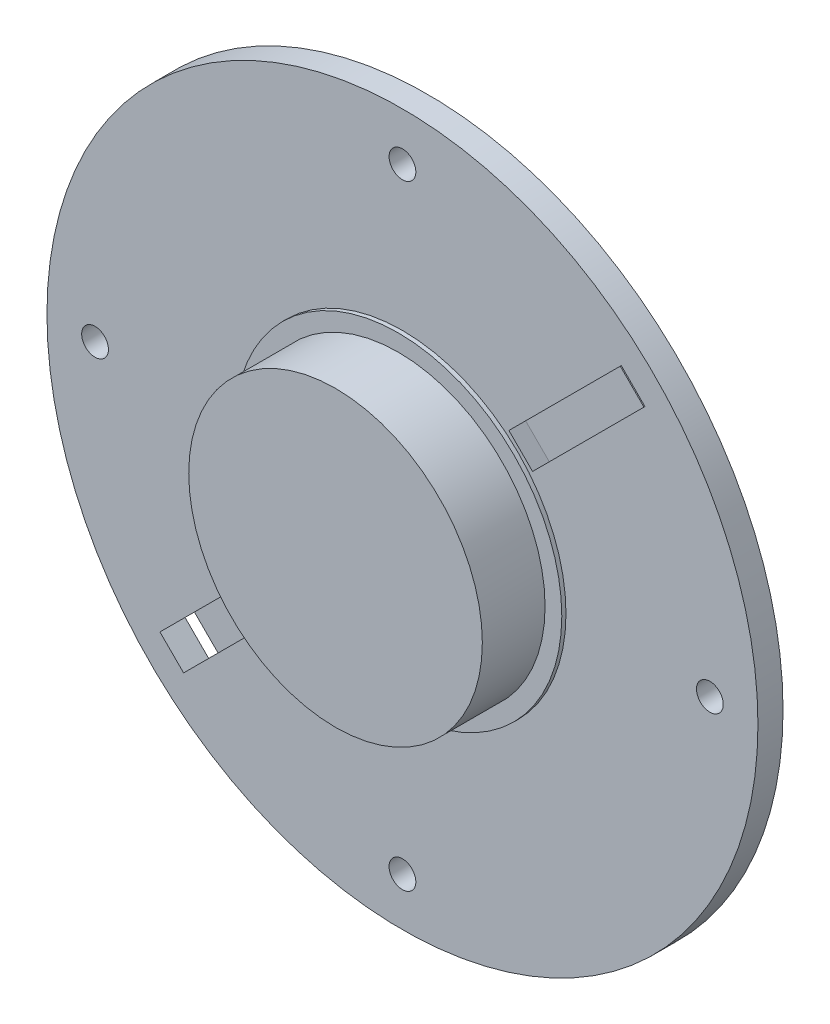
SolidWorks part; units mm, degrees
ref_plane "Front Plane" through (0, 0, 0) normal (0, 0, 1) x (1, 0, 0)
ref_plane "Top Plane" through (0, 0, 0) normal (0, 1, 0) x (1, 0, 0)
ref_plane "Right Plane" through (0, 0, 0) normal (1, 0, 0) x (0, 0, -1)
sketch "Sketch1" plane through (0, 0, 0) normal (1, 0, 0) x (0, 0, -1)
  line L0 (0, 0) -> (0, 42.5)
  line L1 (0, 42.5) -> (-3, 42.5)
  line L2 (-3, 42.5) -> (-3, 19.55)
  line L3 (-3.5, 17.55) -> (-11, 17.55)
  line L4 (-11, 17.55) -> (-11, 0)
  line L5 (-11, 0) -> (0, 0)
  line L6 (0, 0) -> (-73.6158, 0) construction
  line L7 (-3.5, 17.55) -> (-3.5, 19.55)
  line L8 (-3.5, 19.55) -> (-3, 19.55)
  dimension "D1" = 35.1
  dimension "D2" = 85
  dimension "D3" = 3
  dimension "D4" = 8
  dimension "D5" = 0.5
  dimension "D6" = 2
revolve "Revolve1" add sketch "Sketch1" angle 360 about L5
sketch "Sketch2" plane through (0, 0, 0) normal (0, 0, -1) x (-1, 0, 0)
  circle A0 centre (0, 0) radius 36.75 construction
  circle A1 centre (0, 36.75) radius 1.6
  circle A2 centre (36.75, 0) radius 1.6
  circle A3 centre (0, -36.75) radius 1.6
  circle A4 centre (-36.75, 0) radius 1.6
  point P11 (0, 0)
  dimension "D3" = 3.2
extrude "Cut-Extrude1" cut sketch "Sketch2" against normal through all
sketch "Sketch3" [suppressed] plane through (0, 0, 11) normal (0, 0, 1) x (1, 0, 0)
  line L0 (0, -4) -> (0, 4) construction
  line L2 (9, -9) -> (-9, -9) construction
  line L3 (9, -9) -> (9, 9) construction
  line L4 (9, 9) -> (-9, 9) construction
  line L5 (-9, -9) -> (-9, 9) construction
  line L6 (9, -9) -> (-9, 9) construction
  line L7 (9, 9) -> (-9, -9) construction
  circle A0 centre (0, 4) radius 2.4
  circle A1 centre (0, -4) radius 2.4
  circle A2 centre (-9, 9) radius 2.4
  circle A3 centre (9, 9) radius 2.4
  circle A4 centre (9, -9) radius 2.4
  circle A5 centre (-9, -9) radius 2.4
  point P0 (0, 0)
  point P10 (0, 0)
  dimension "D1" = 4.8
  dimension "D3" = 4.8
  dimension "8" = 8
  dimension "D4" = 18
extrude "Cut-Extrude2" [suppressed] cut sketch "Sketch3" against normal blind 4
sketch "Sketch5" [suppressed] plane through (0, 0, 3) normal (0, 0, -1) x (-1, 0, 0)
  line L0 (-5.1962, 34.5) -> (-32.476, -12.75)
  line L6 (5.1962, 34.5) -> (32.476, -12.75)
  line L7 (-27.2798, -21.75) -> (27.2798, -21.75)
  arc A0 (5.1962, 34.5) -> (-5.1962, 34.5) centre (0, 31.5) ccw
  arc A1 (-32.476, -12.75) -> (-27.2798, -21.75) centre (-27.2798, -15.75) ccw
  arc A2 (27.2798, -21.75) -> (32.476, -12.75) centre (27.2798, -15.75) ccw
  circle A3 centre (0, 0) radius 17.55 construction
  circle A4 centre (0, 0) radius 17.55 construction
  dimension "D1" = 12
extrude "Cut-Extrude4" [suppressed] cut sketch "Sketch5" along normal through all flip side to cut
chamfer "Chamfer1" [suppressed] distance 0.5 angle 45
sketch "Sketch6" [suppressed] plane through (0, 0, 3) normal (0, 0, 1) x (1, 0, 0)
  circle A0 centre (-27.2798, -15.75) radius 1.6 construction
  circle A1 centre (27.2798, -15.75) radius 1.6 construction
  circle A2 centre (0, 31.5) radius 1.6 construction
  circle A3 centre (-27.2798, -15.75) radius 1.6
  circle A4 centre (27.2798, -15.75) radius 1.6
  circle A5 centre (0, 31.5) radius 1.6
  circle A6 centre (0, 31.5) radius 3
  circle A7 centre (-27.2798, -15.75) radius 3
  circle A8 centre (27.2798, -15.75) radius 3
  dimension "D1" = 6
extrude "Boss-Extrude1" [suppressed] add sketch "Sketch6" along normal blind 2
fillet "Fillet1" [suppressed] radius 1
sketch "Sketch7" [suppressed] plane through (0, 0, 11) normal (0, 0, 1) x (1, 0, 0)
  circle A0 centre (-9, 9) radius 1.75
  circle A1 centre (0, 4) radius 1.75
  circle A2 centre (9, 9) radius 1.75
  circle A3 centre (9, -9) radius 1.75
  circle A4 centre (-9, -9) radius 1.75
  circle A5 centre (0, -4) radius 1.75
  dimension "D1" = 3.5
extrude "Cut-Extrude5" [suppressed] cut sketch "Sketch7" against normal blind 6
sketch "Sketch8" plane through (0, 0, 0) normal (0, 0, -1) x (-1, 0, 0)
  circle A0 centre (0, 0) radius 10
  dimension "D1" = 20
extrude "Cut-Extrude6" cut sketch "Sketch8" against normal blind 2
sketch "Sketch16" plane through (0, 0, 2) normal (0, 0, -1) x (-1, 0, 0)
  line L0 (-4.0659, -4.0659) -> (4.0659, 4.0659) construction
  line L1 (0, 0) -> (0, 18.7038) construction
  circle A0 centre (4.0659, 4.0659) radius 1.5
  circle A1 centre (-4.0659, -4.0659) radius 1.5
  point P4 (0, 0)
  dimension "D1" = 3
  dimension "D2" = 45
  dimension "D3" = 11.5
extrude "Cut-Extrude7" cut sketch "Sketch16" against normal blind 4
ref_plane "Plane1" through (0, 0, 0) normal (-0.7071, 0.7071, 0) x (0, 0, 1)
sketch "Sketch19" plane through (0, 0, 0) normal (-0.7071, 0.7071, 0) x (0, 0, 1)
  line L0 (0, -15) -> (0, 15)
  line L1 (0, 42.5) -> (0, -42.5) construction
  line L2 (0, 15) -> (1, 20)
  line L3 (1, 20) -> (1, 36)
  line L4 (1, 36) -> (0, 36)
  line L5 (0, 36) -> (0, 39)
  line L6 (0, 39) -> (3, 39)
  line L7 (3, -42.5) -> (3, 42.5) construction
  line L8 (3, 39) -> (3, 20)
  line L9 (3, 20) -> (2, 15)
  line L10 (2, 15) -> (2, -15)
  line L11 (2, 0) -> (0, 0) construction
  line L12 (1, -36) -> (0, -36)
  line L13 (0, -36) -> (0, -39)
  line L14 (0, -39) -> (3, -39)
  line L15 (1, -20) -> (1, -36)
  line L16 (3, -39) -> (3, -20)
  line L17 (3, -20) -> (2, -15)
  line L18 (0, -15) -> (1, -20)
  dimension "D1" = 2
  dimension "D2" = 15
  dimension "D3" = 2
  dimension "20" = 20
  dimension "D4" = 3
  dimension "D5" = 39
  dimension "D6" = 15
extrude "Cut-Extrude10" cut sketch "Sketch19" against normal mid plane 4
sketch "Sketch20" plane through (0, 0, 0) normal (0, 0, -1) x (-1, 0, 0)
  line L0 (-28.9914, 26.163) -> (-24.0416, 26.8701) construction
  line L1 (24.0416, -26.8701) -> (28.9914, -26.163) construction
  point P8 (26.5165, -26.5165)
  point P9 (-26.5165, 26.5165)
equation "\"D1@Sketch2\"   = (\"Sun Teeth@Wheel Assembly-1.Assembly\"+\"Planet Teeth 2@Wheel Assembly-1.Assembly\" ) * \"Module@Wheel Assembly-1.Assembly\""
